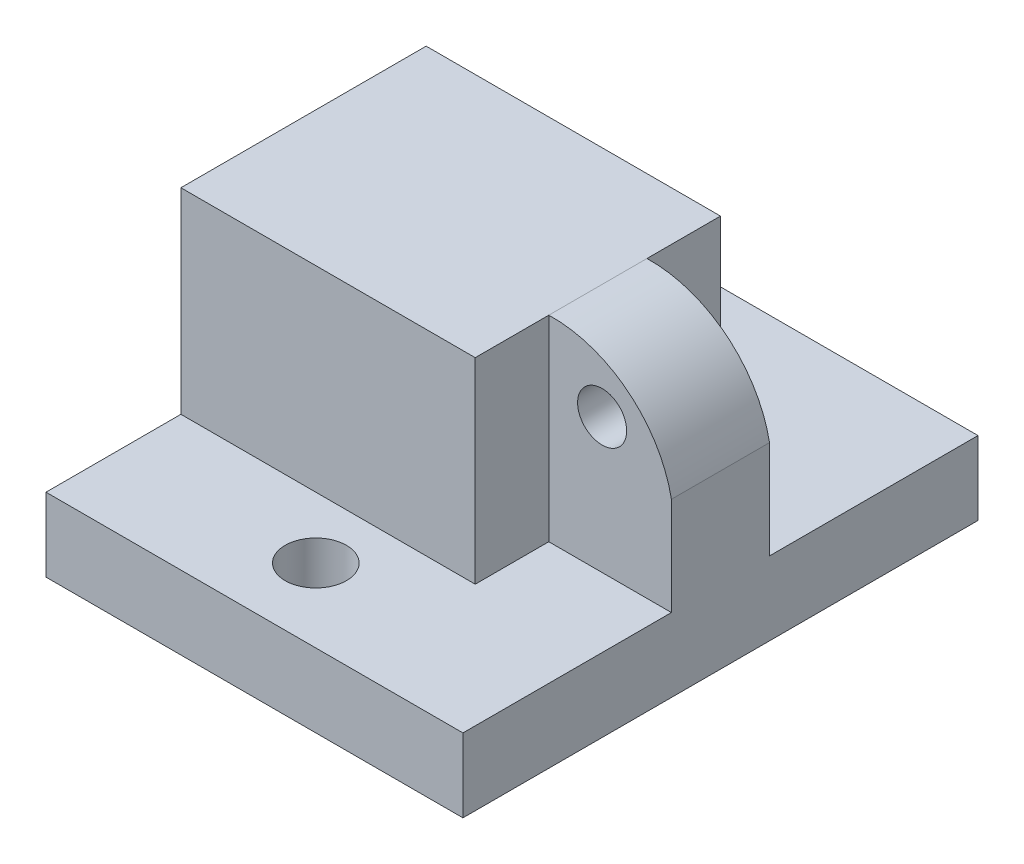
SolidWorks part; units mm, degrees
ref_plane "Front Plane" through (0, 0, 0) normal (0, 0, 1) x (1, 0, 0)
ref_plane "Top Plane" through (0, 0, 0) normal (0, 1, 0) x (1, 0, 0)
ref_plane "Right Plane" through (0, 0, 0) normal (1, 0, 0) x (0, 0, -1)
sketch "Sketch2" plane through (0, 0, 0) normal (0, 1, 0) x (1, 0, 0)
  line L1 (0, 0) -> (17, 0)
  line L2 (0, 0) -> (0, 21)
  line L3 (0, 21) -> (17, 21)
  line L4 (17, 0) -> (17, 21)
  dimension "D1" = 21
  dimension "D2" = 17
extrude "Boss-Extrude1" add sketch "Sketch2" along normal blind 3
sketch "Sketch3" plane through (0, 3, 0) normal (0, 1, 0) x (1, 0, 0)
  line L0 (0, 21) -> (0, 0) construction
  line L1 (0, 13) -> (17, 13)
  line L2 (0, 13) -> (0, -1)
  line L3 (0, -1) -> (17, -1)
  line L4 (17, 13) -> (17, -1)
  line L5 (17, 0) -> (17, 21) construction
  line L6 (17, 21) -> (0, 21) construction
  dimension "D1" = 14
  dimension "D2" = 8
extrude "Boss-Extrude2" [suppressed] add sketch "Sketch3" along normal blind 6
sketch "Sketch4" plane through (0, 3, 0) normal (0, 1, 0) x (1, 0, 0)
  line L0 (17, 21) -> (0, 21) construction
  line L1 (17, 0) -> (17, 21) construction
  circle A0 centre (8, 18) radius 1.25
  dimension "D1" = 2.5
  dimension "D2" = 3
  dimension "D3" = 9
sketch "Sketch5" plane through (0, 3, 0) normal (0, 1, 0) x (1, 0, 0)
  line L0 (17, 0) -> (17, 21) construction
  line L1 (0, 0) -> (17, 0) construction
  circle A0 centre (8, 3) radius 1.25
  dimension "D1" = 2.5
  dimension "D2" = 9
  dimension "D3" = 3
extrude "Cut-Extrude1" cut sketch "Sketch4" against normal blind 6 contours A0
extrude "Cut-Extrude2" cut sketch "Sketch5" against normal blind 6 contours A0
sketch "Sketch6" plane through (0, 3, 0) normal (0, 1, 0) x (1, 0, 0)
  line L0 (0, 21) -> (0, 0) construction
  line L1 (0, 15.5) -> (12, 15.5)
  line L2 (0, 15.5) -> (0, 5.5)
  line L3 (0, 5.5) -> (12, 5.5)
  line L4 (12, 15.5) -> (12, 5.5)
  line L5 (17, 21) -> (0, 21) construction
  dimension "D1" = 12
  dimension "D2" = 10
  dimension "D3" = 5.5
extrude "Boss-Extrude3" add sketch "Sketch6" along normal blind 8
sketch "Sketch7" plane through (0, 3, 0) normal (0, 1, 0) x (1, 0, 0)
  line L0 (17, 0) -> (17, 21) construction
  line L1 (17, 12.5) -> (12, 12.5)
  line L2 (17, 12.5) -> (17, 8.5)
  line L3 (17, 8.5) -> (12, 8.5)
  line L4 (12, 12.5) -> (12, 8.5)
  line L5 (12, 5.5) -> (12, 15.5) construction
  line L6 (17, 21) -> (0, 21) construction
  dimension "D1" = 4
  dimension "D2" = 8.5
extrude "Boss-Extrude4" add sketch "Sketch7" along normal blind 4
ref_plane "Plane2" through (0, 0, -12.5) normal (0, 0, -1) x (-1, 0, 0)
sketch "Sketch8" plane through (0, 0, -12.5) normal (0, 0, -1) x (-1, 0, 0)
  line L0 (-17, 7) -> (-12, 7) construction
  line L1 (-17, 7) -> (-12, 7)
  line L2 (-12, 7) -> (-12, 11)
  arc A0 (-12, 11) -> (-17, 7) centre (-12.1431, 6.0539) ccw
  point P8 (0, 0)
  point P9 (-17, 10)
extrude "Boss-Extrude5" add sketch "Sketch8" against normal blind 4
sketch "Sketch9" plane through (0, 0, -8.5) normal (0, 0, 1) x (1, 0, 0)
  line L0 (12, 3) -> (17, 3) construction
  circle A0 centre (14.1744, 8.5) radius 1
  dimension "D1" = 2
  dimension "D2" = 5.5
extrude "Cut-Extrude3" cut sketch "Sketch9" against normal blind 6
